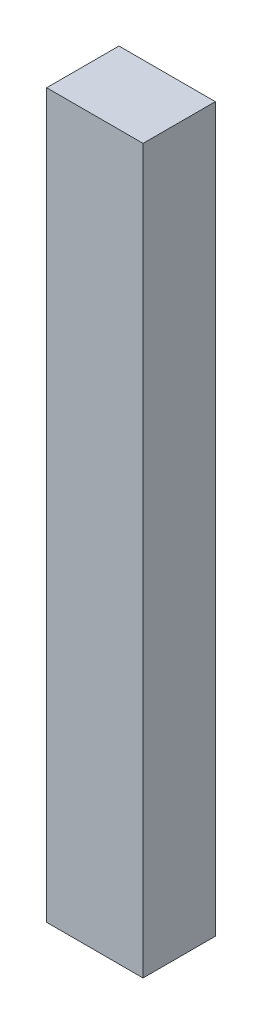
SolidWorks part; units mm, degrees
ref_plane "Front Plane" through (0, 0, 0) normal (1, 0, 0) x (0, 1, 0)
ref_plane "Top Plane" through (0, 0, 0) normal (0, 0, 1) x (0, 1, 0)
ref_plane "Right Plane" through (0, 0, 0) normal (0, 1, 0) x (-1, 0, 0)
sketch "Sketch1" plane through (0, 0, 0) normal (0, 1, 0) x (-1, 0, 0)
  line L1 (-4, 3) -> (4, 3)
  line L2 (-4, 3) -> (-4, -3)
  line L3 (-4, -3) -> (4, -3)
  line L4 (4, 3) -> (4, -3)
  point P4 (0, 3)
  point P6 (4, 0)
  dimension "D1" = 6
  dimension "D2" = 8
extrude "Boss-Extrude1" add sketch "Sketch1" along normal mid plane 60
